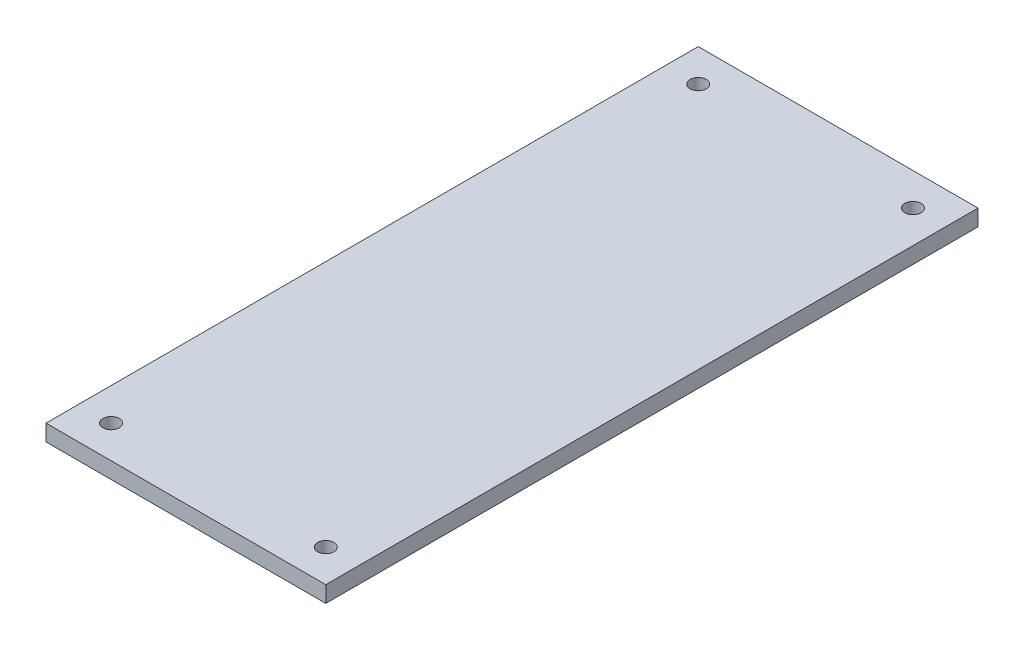
SolidWorks part; units mm, degrees
material "아크릴(내충격성)"
ref_plane "정면" through (0, 0, 0) normal (0, 0, 1) x (1, 0, 0)
ref_plane "윗면" through (0, 0, 0) normal (0, 1, 0) x (1, 0, 0)
ref_plane "우측면" through (0, 0, 0) normal (1, 0, 0) x (0, 0, -1)
sketch "스케치1" plane through (0, 0, 0) normal (0, 1, 0) x (1, 0, 0)
  line L1 (-43, 100.25) -> (43, 100.25)
  line L2 (-43, 100.25) -> (-43, -100.25)
  line L3 (-43, -100.25) -> (43, -100.25)
  line L4 (43, 100.25) -> (43, -100.25)
  line L5 (-43, 100.25) -> (43, -100.25) construction
  line L6 (-43, -100.25) -> (43, 100.25) construction
  point P0 (0, 0)
  dimension "D1" = 86
  dimension "D2" = 200.5
extrude "보스-돌출1" add sketch "스케치1" along normal blind 5
sketch "스케치2" plane through (0, 5, 0) normal (0, 1, 0) x (1, 0, 0)
  line L0 (43, 100.25) -> (-43, 100.25) construction
  line L1 (-43, 100.25) -> (-43, -100.25) construction
  line L2 (43, -100.25) -> (43, 100.25) construction
  line L3 (-43, -100.25) -> (43, -100.25) construction
  circle A0 centre (-33, 90.25) radius 2.5
  circle A1 centre (33, 90.25) radius 2.5
  circle A2 centre (-33, -90.25) radius 2.5
  circle A3 centre (33, -90.25) radius 2.5
  point P16 (0, 0)
  point P18 (-40.25, -88.1024)
  dimension "D1" = 10
  dimension "D2" = 10
  dimension "D3" = 10
  dimension "D4" = 10
  dimension "D5" = 10
  dimension "D6" = 10
  dimension "D7" = 10
  dimension "D8" = 10
extrude "컷-돌출1" cut sketch "스케치2" against normal through all
